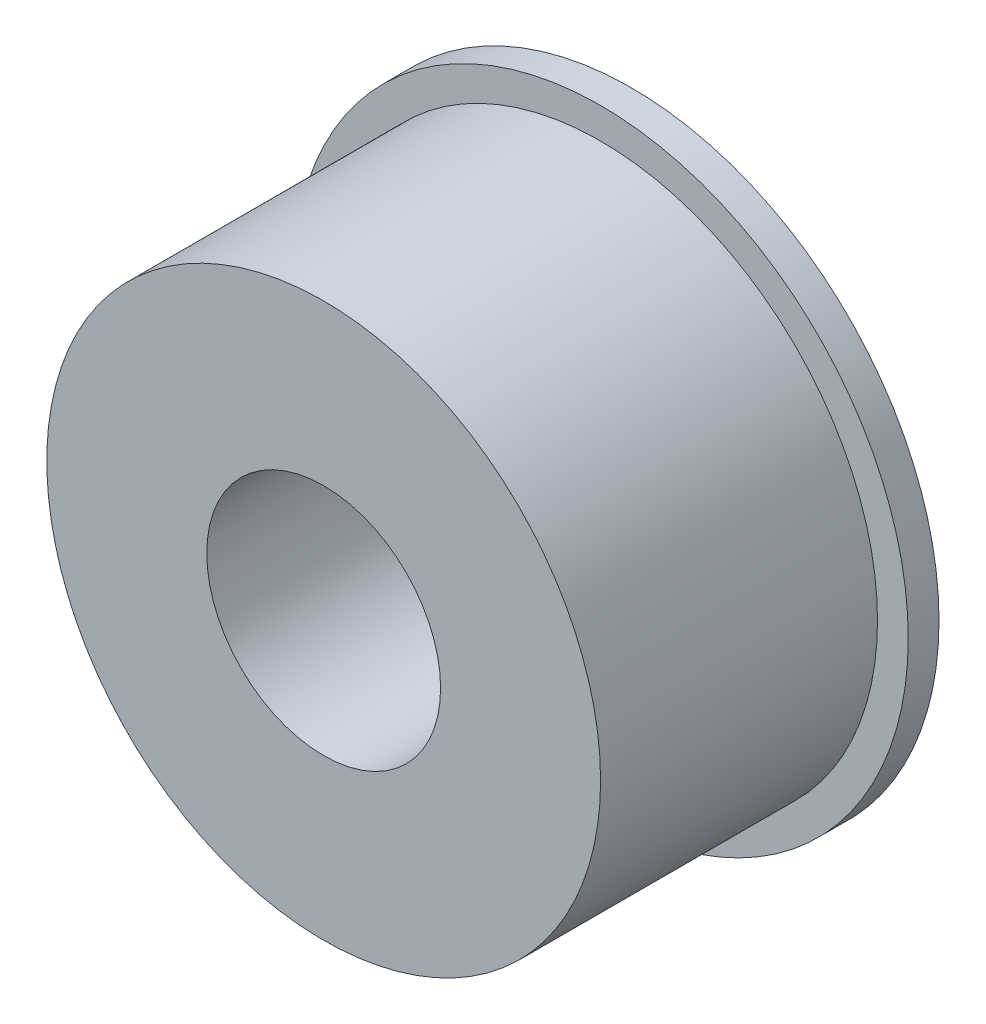
SolidWorks part; units mm, degrees
ref_plane "Front Plane" through (0, 0, 0) normal (0, 0, 1) x (1, 0, 0)
ref_plane "Top Plane" through (0, 0, 0) normal (0, 1, 0) x (1, 0, 0)
ref_plane "Right Plane" through (0, 0, 0) normal (1, 0, 0) x (0, 0, -1)
sketch "Sketch1" plane through (0, 0, 0) normal (0, 0, 1) x (1, 0, 0)
  circle A0 centre (0, 0) radius 25.4
extrude "Boss-Extrude1" add sketch "Sketch1" along normal blind 2.54
sketch "Sketch2" plane through (0, 0, 2.54) normal (0, 0, 1) x (1, 0, 0)
  circle A0 centre (0, 0) radius 22.86
extrude "Boss-Extrude2" add sketch "Sketch2" along normal blind 22.86
sketch "Sketch3" plane through (0, 0, 25.4) normal (0, 0, 1) x (1, 0, 0)
  circle A0 centre (0, 0) radius 9.652
extrude "Cut-Extrude1" cut sketch "Sketch3" against normal blind 30.734
